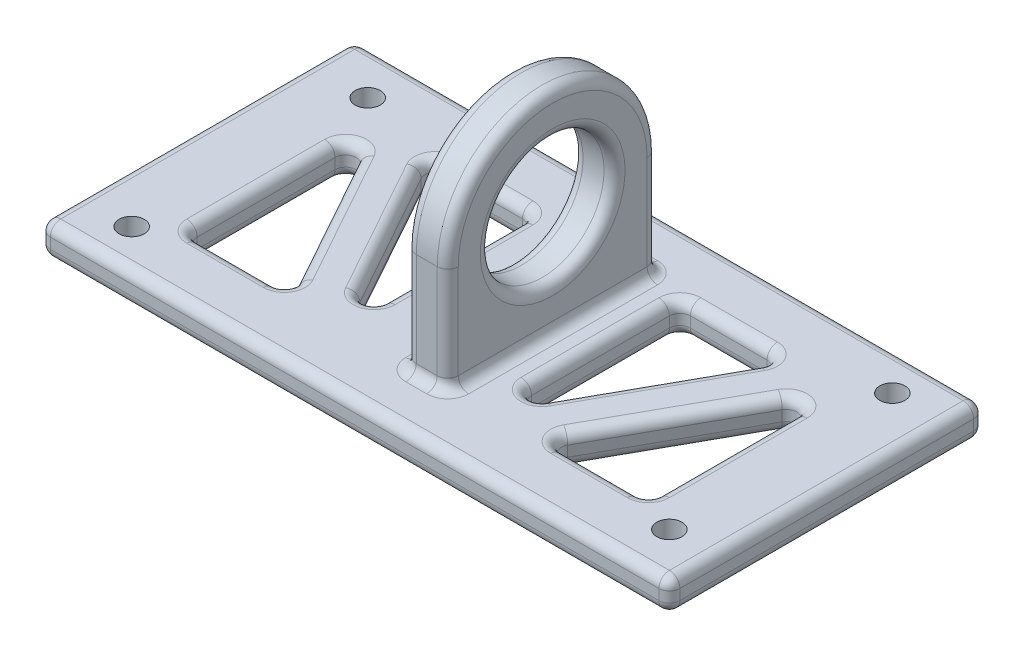
SolidWorks part; units mm, degrees
ref_plane "Front Plane" through (0, 0, 0) normal (0, 0, 1) x (1, 0, 0)
ref_plane "Top Plane" through (0, 0, 0) normal (0, 1, 0) x (1, 0, 0)
ref_plane "Right Plane" through (0, 0, 0) normal (1, 0, 0) x (0, 0, -1)
sketch "Sketch1" plane through (0, 0, 0) normal (0, 1, 0) x (1, 0, 0)
  line L1 (38.1, 19.05) -> (-38.1, 19.05)
  line L2 (38.1, 19.05) -> (38.1, -19.05)
  line L3 (38.1, -19.05) -> (-38.1, -19.05)
  line L4 (-38.1, 19.05) -> (-38.1, -19.05)
  line L5 (38.1, 19.05) -> (-38.1, -19.05) construction
  line L6 (38.1, -19.05) -> (-38.1, 19.05) construction
  point P0 (0, 0)
  dimension "D1" = 38.1
  dimension "D2" = 76.2
extrude "Boss-Extrude1" add sketch "Sketch1" along normal blind 3.81
sketch "Sketch2" plane through (0, 3.81, 0) normal (0, 1, 0) x (1, 0, 0)
  line L0 (38.1, -19.05) -> (38.1, 19.05) construction
  line L1 (38.1, 19.05) -> (-38.1, 19.05) construction
  line L2 (-38.1, -19.05) -> (38.1, -19.05) construction
  line L3 (-38.1, 19.05) -> (-38.1, -19.05) construction
  circle A0 centre (31.75, 14.2875) radius 1.524
  circle A1 centre (32.5438, -13.4938) radius 1.524
  circle A2 centre (-31.75, -14.2875) radius 1.524
  circle A3 centre (-30.9563, 13.4938) radius 1.524
  dimension "D1" = 3.048
  dimension "D4" = 3.048
  dimension "D7" = 3.048
  dimension "D10" = 3.048
  dimension "D2" = 6.35
  dimension "D3" = 4.7625
  dimension "D5" = 5.5562
  dimension "D6" = 5.5562
  dimension "D8" = 6.35
  dimension "D9" = 4.7625
  dimension "D11" = 5.5562
  dimension "D12" = 7.1437
extrude "Cut-Extrude1" cut sketch "Sketch2" against normal through all
sketch3d "3DSketch1" plane through (0, 0, 0) normal (0, 0, 1) x (1, 0, 0)
  dimension "D1" = 35.7188
sketch "Sketch4" plane through (2.3813, 0, 0) normal (1, 0, 0) x (0, 0, -1)
  line L0 (-19.05, 3.81) -> (19.05, 3.81) construction
  line L1 (-12.7, 16.51) -> (12.7, 16.51)
  line L2 (-12.7, 16.51) -> (-12.7, 3.81)
  line L3 (-12.7, 3.81) -> (12.7, 3.81)
  line L4 (12.7, 16.51) -> (12.7, 3.81)
  line L5 (-12.7, 16.51) -> (12.7, 3.81) construction
  line L6 (-12.7, 3.81) -> (12.7, 16.51) construction
  point P0 (0, 10.16)
  dimension "D1" = 12.7
  dimension "D2" = 25.4
extrude "Boss-Extrude2" add sketch "Sketch4" along normal mid plane 5.08
ref_plane "Plane1" through (4.9213, 16.51, -12.7) normal (-1, 0, 0) x (0, 0, 1)
sketch "Sketch5" plane through (4.9213, 16.51, -12.7) normal (-1, 0, 0) x (0, 0, 1)
  line L0 (0, 0) -> (25.4, 0) construction
  line L1 (0, -12.7) -> (0, 0) construction
  line L2 (0, 0) -> (25.4, 0)
  arc A0 (25.4, 0) -> (0, 0) centre (12.7, 0) ccw
extrude "Boss-Extrude3" add sketch "Sketch5" along normal up to surface (5.08 mm away) up to face at (-0.1587, 10.16, 0)
sketch "Sketch6" plane through (4.9213, 16.51, -12.7) normal (-1, 0, 0) x (0, 0, 1)
  circle A0 centre (12.7, 0) radius 7.493
  dimension "D1" = 14.986
extrude "Cut-Extrude2" cut sketch "Sketch6" against normal through all both and the other way through all
fillet "Fillet1" radius 1.27 24 edges at (4.9213, 10.16, -12.7) (-0.1587, 29.21, 0) (4.9213, 29.21, 0) (-0.1587, 10.16, 12.7) (-0.1587, 16.51, -7.493) (4.9213, 16.51, -7.493) (4.9213, 10.16, 12.7) (-0.1587, 10.16, -12.7) (2.3813, 3.81, -12.7) (-0.1587, 3.81, 0) (2.3813, 3.81, 12.7) (4.9213, 3.81, 0) (-38.1, 1.905, 19.05) (-38.1, 3.81, 0) (-38.1, 0, 0) (-38.1, 1.905, -19.05) (0, 0, -19.05) (0, 3.81, -19.05) (38.1, 1.905, -19.05) (38.1, 3.81, 0) (38.1, 0, 0) (38.1, 1.905, 19.05) (0, 0, 19.05) (0, 3.81, 19.05)
sketch "Sketch8" plane through (4.9213, 16.51, -12.7) normal (-1, 0, 0) x (0, 0, 1)
  line L0 (0.0305, -16.51) -> (25.4305, -16.51)
  line L1 (-5.08, -16.51) -> (30.48, -16.51) construction
  line L2 (25.4305, -16.51) -> (25.4305, -29.21)
  line L3 (0.0305, -16.51) -> (0.0305, -29.21)
  arc A0 (25.4305, -29.21) -> (0.0305, -29.21) centre (12.7305, -29.21) cw
  dimension "D3" = 12.7
  dimension "D1" = 12.7
  dimension "D2" = 25.4
extrude "Boss-Extrude4" [suppressed] add sketch "Sketch8" along normal blind 5.08
sketch "Sketch9" [suppressed] plane through (4.4133, 0, 0) normal (1, 0, 0) x (0, 0, -1)
  circle A0 centre (-0.0305, -12.7) radius 7.493
  dimension "D1" = 14.986
extrude "Cut-Extrude3" [suppressed] cut sketch "Sketch9" against normal through all both and the other way through all
sketch "Sketch10" plane through (0, 3.81, 0) normal (0, 1, 0) x (1, 0, 0)
  line L0 (-27.94, -11.43) -> (-27.94, 11.43)
  line L1 (-27.94, 11.43) -> (-15.24, -11.43)
  line L2 (-15.24, -11.43) -> (-27.94, -11.43)
  line L3 (-36.83, -17.78) -> (36.83, -17.78) construction
  line L4 (-36.83, 17.78) -> (-36.83, -17.78) construction
  line L5 (27.94, 11.43) -> (15.24, -11.43)
  line L6 (-21.59, 11.43) -> (-8.89, -11.43)
  line L7 (-8.89, -11.43) -> (-8.89, 11.43)
  line L8 (-8.89, 11.43) -> (-21.59, 11.43)
  line L9 (8.89, 11.43) -> (8.89, -11.43)
  line L10 (8.89, -11.43) -> (21.59, 11.43)
  line L11 (21.59, 11.43) -> (8.89, 11.43)
  line L12 (36.83, 17.78) -> (-36.83, 17.78) construction
  line L13 (15.24, -11.43) -> (27.94, -11.43)
  line L14 (36.83, -17.78) -> (36.83, 17.78) construction
  line L15 (27.94, -11.43) -> (27.94, 11.43)
  dimension "D1" = 12.7
  dimension "D2" = 22.86
  dimension "D3" = 6.35
  dimension "D4" = 8.89
  dimension "D5" = 12.7
  dimension "D6" = 22.86
  dimension "D8" = 22.86
  dimension "D9" = 12.7
  dimension "D10" = 22.86
  dimension "D11" = 6.35
  dimension "D12" = 6.35
  dimension "D13" = 27.94
  dimension "D14" = 12.7
  dimension "D16" = 8.89
  dimension "D17" = 27.94
extrude "Cut-Extrude4" cut sketch "Sketch10" against normal through all both and the other way through all
fillet "Fillet2" radius 1.27 36 edges at (27.94, 1.905, 11.43) (15.24, 1.905, 11.43) (8.89, 1.905, 11.43) (27.94, 1.905, -11.43) (21.59, 1.905, -11.43) (8.89, 1.905, -11.43) (-27.94, 1.905, 11.43) (-15.24, 1.905, 11.43) (-8.89, 1.905, 11.43) (-8.89, 1.905, -11.43) (-21.59, 1.905, -11.43) (-27.94, 1.905, -11.43) (-21.59, 0, 0) (-21.59, 0, 11.43) (-15.24, 0, 0) (-15.24, 0, -11.43) (27.94, 0, 0) (21.59, 0, 11.43) (15.24, 0, -11.43) (15.24, 0, 0) (21.59, 3.81, 11.43) (27.94, 3.81, 0) (15.24, 3.81, 0) (15.24, 3.81, -11.43) (-21.59, 3.81, 11.43) (-21.59, 3.81, 0) (-8.89, 3.81, 0) (-15.24, 3.81, -11.43) (-27.94, 0, 0) (-8.89, 0, 0) (21.59, 0, 0) (8.89, 0, 0) (21.59, 3.81, 0) (8.89, 3.81, 0) (-27.94, 3.81, 0) (-15.24, 3.81, 0)
equation "\"0.105n\"=0.1"
